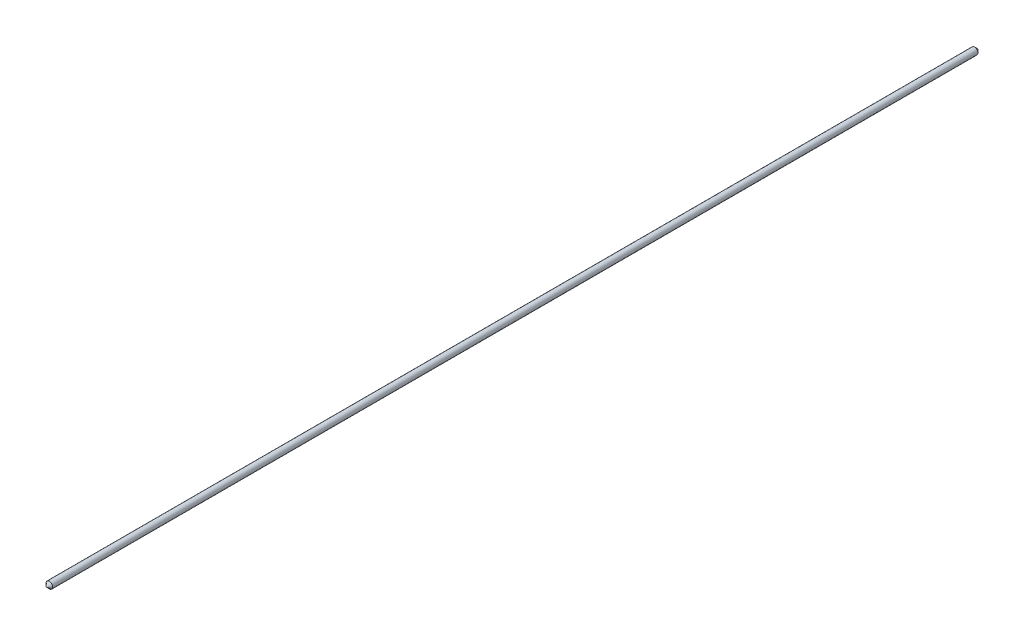
SolidWorks part; units mm, degrees
ref_plane "Front Plane" through (0, 0, 0) normal (0, 0, 1) x (1, 0, 0)
ref_plane "Top Plane" through (0, 0, 0) normal (0, 1, 0) x (1, 0, 0)
ref_plane "Right Plane" through (0, 0, 0) normal (1, 0, 0) x (0, 0, -1)
sketch "Sketch1" plane through (0, 0, 0) normal (1, 0, 0) x (0, 0, -1)
  line L0 (-32.3677, 0) -> (-22.6669, 10)
  line L1 (55, 0) -> (-55, 0) construction
  line L4 (-22.6669, 10) -> (2743.6403, 10)
  line L5 (2743.6403, 10) -> (2753.9523, 0)
  line L6 (2753.9523, 0) -> (2057.6601, 0)
  line L8 (-32.3677, 0) -> (2057.6601, 0)
  point P6 (0, 0)
  point P10 (0, 0)
  dimension "D2" = 44.12
  dimension "D3" = 2786.32
  dimension "D4" = 10
revolve "Revolve1" add sketch "Sketch1" angle 360 about L8
ref_plane "Plane1" through (0, 0, 32.3677) normal (0, 0, 1) x (1, 0, 0)
